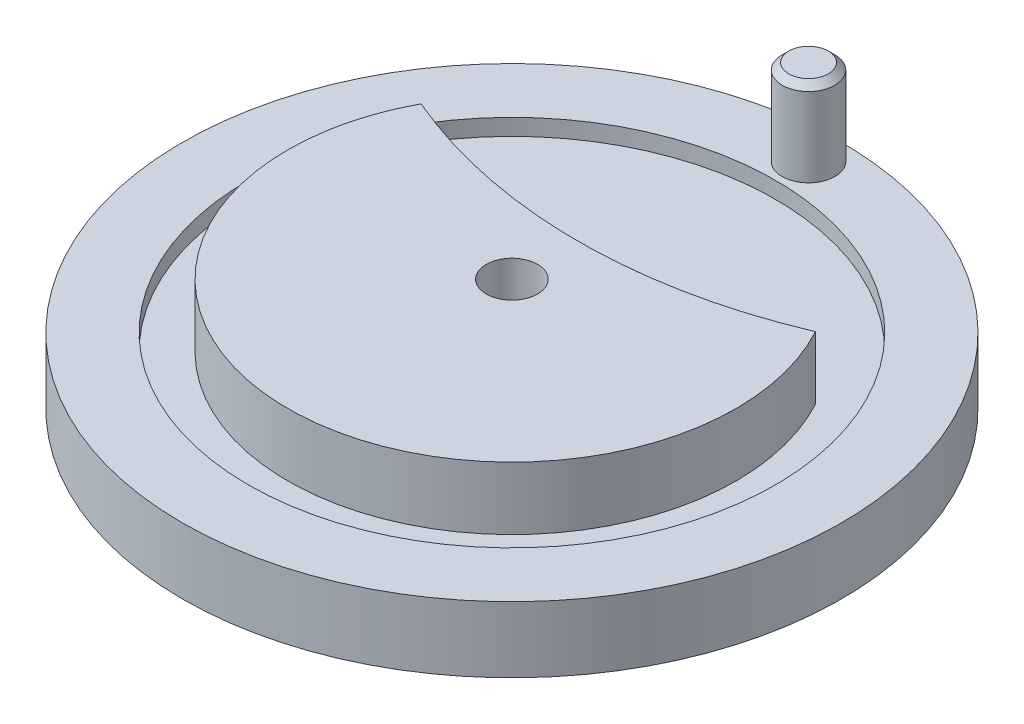
SolidWorks part; units mm, degrees
material "Nylon 101"
ref_plane "Front Plane" through (0, 0, 0) normal (0, 0, 1) x (1, 0, 0)
ref_plane "Top Plane" through (0, 0, 0) normal (0, 1, 0) x (1, 0, 0)
ref_plane "Right Plane" through (0, 0, 0) normal (1, 0, 0) x (0, 0, -1)
sketch "Sketch1" plane through (0, 0, 0) normal (0, 1, 0) x (1, 0, 0)
  circle A0 centre (0, 0) radius 31.75
  circle A1 centre (0, 0) radius 2.4765
  dimension "D1" = 63.5
  dimension "D2" = 4.953
extrude "Boss-Extrude1" add sketch "Sketch1" along normal blind 6.35
sketch "Sketch2" plane through (0, 6.35, 0) normal (0, 1, 0) x (1, 0, 0)
  circle A0 centre (0, 0) radius 25.4
  dimension "D1" = 50.8
extrude "Cut-Extrude1" cut sketch "Sketch2" against normal blind 1.5875
sketch "Sketch3" plane through (0, 4.7625, 0) normal (0, 1, 0) x (1, 0, 0)
  arc A0 (-19.0025, 10.2486) -> (19.0025, 10.2486) centre (0, 0) ccw
  arc A1 (-19.0025, 10.2486) -> (19.0025, 10.2486) centre (0, 54.61) ccw
  circle A2 centre (0, 0) radius 2.4765 construction
  circle A3 centre (0, 0) radius 2.4765
  dimension "D1" = 43.18
  dimension "D2" = 96.52
  dimension "D3" = 54.61
extrude "Boss-Extrude2" add sketch "Sketch3" along normal blind 6.0452
sketch "Sketch4" plane through (0, 6.35, 0) normal (0, 1, 0) x (1, 0, 0)
  circle A0 centre (0, 28.575) radius 2.54
  dimension "D1" = 5.08
  dimension "D2" = 28.575
extrude "Boss-Extrude3" add sketch "Sketch4" along normal blind 8.255
chamfer "Chamfer1" distance 0.635 angle 45 1 edges at (0, 14.605, -26.035)
sketch "Sketch5" plane through (0, 0, 0) normal (0, -1, 0) x (1, 0, 0)
  circle A0 centre (0, 0) radius 6.35
  dimension "D1" = 12.7
extrude "Boss-Extrude4" add sketch "Sketch5" along normal blind 3.302
sketch "Sketch6" plane through (0, -3.302, 0) normal (0, -1, 0) x (1, 0, 0)
  circle A0 centre (0, 0) radius 4.445
  dimension "D1" = 8.89
extrude "Cut-Extrude2" cut sketch "Sketch6" against normal blind 6.604
